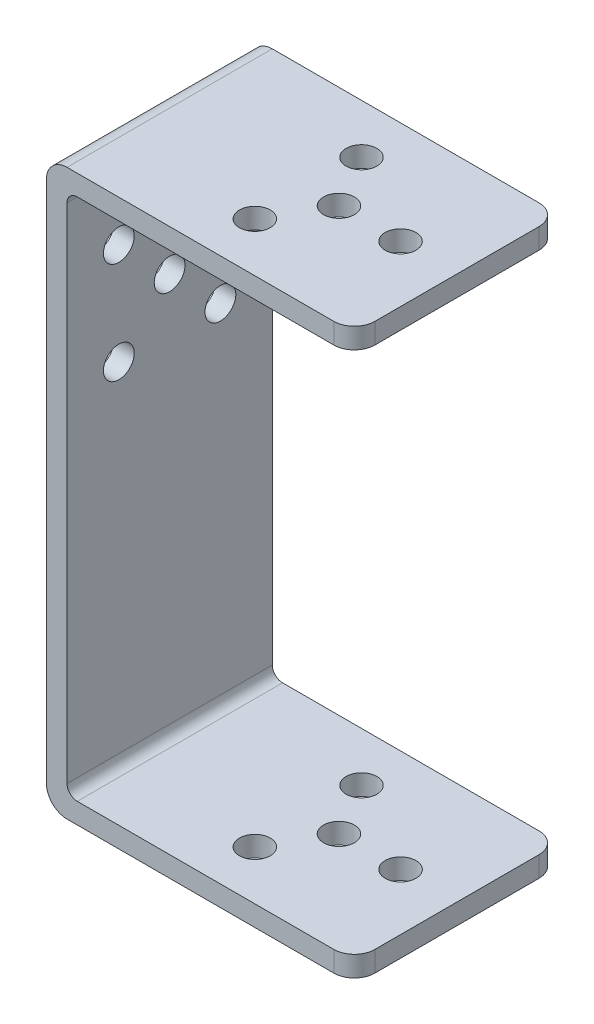
SolidWorks part; units mm, degrees
ref_plane "前视基准面" through (0, 0, 0) normal (0, 0, 1) x (1, 0, 0)
ref_plane "上视基准面" through (0, 0, 0) normal (0, 1, 0) x (1, 0, 0)
ref_plane "右视基准面" through (0, 0, 0) normal (1, 0, 0) x (0, 0, -1)
other "Configuration Table"
sketch "草图1" plane through (0, 0, 0) normal (0, 0, 1) x (1, 0, 0)
  line L0 (0, 0) -> (30, 0)
  line L1 (30, 0) -> (30, 2)
  line L2 (30, 2) -> (2, 2)
  line L3 (2, 2) -> (2, 53)
  line L4 (2, 53) -> (30, 53)
  line L5 (30, 53) -> (30, 55)
  line L6 (30, 55) -> (0, 55)
  line L7 (0, 55) -> (0, 0)
  dimension "D1" = 55
  dimension "D2" = 2
  dimension "D3" = 2
  dimension "D4" = 2
  dimension "D5" = 30
  dimension "D6" = 30
extrude "凸台-拉伸1" add sketch "草图1" along normal blind 20
sketch "草图2" plane through (0, 0, 0) normal (-1, 0, 0) x (0, 0, 1)
  line L0 (10, 55) -> (10, 0) construction
  line L1 (20, 55) -> (0, 55) construction
  line L2 (20, 0) -> (0, 0) construction
  line L3 (5.0503, 45.9497) -> (10, 41) construction
  circle A0 centre (10, 41) radius 1.5
  circle A1 centre (5.0503, 45.9497) radius 1.5
  circle A12 centre (14.9497, 45.9497) radius 1.5
  circle A13 centre (14.9497, 36.0503) radius 1.5
  circle A14 centre (5.0503, 36.0503) radius 1.5
  point P19 (10, 41)
  point P20 (10, 41)
  point P21 (10, 41)
  dimension "D3" = 3
  dimension "D4" = 3
  dimension "D1" = 41
  dimension "D2" = 45
  dimension "D5" = 7
  dimension "D6" = 4
extrude "切除-拉伸1" cut sketch "草图2" against normal blind 10
sketch "草图4" plane through (0, 55, 0) normal (0, 1, 0) x (1, 0, 0)
  line L0 (30, -20) -> (30, 0) construction
  line L1 (15, -10) -> (30, -10) construction
  line L2 (30, 0) -> (0, 0) construction
  circle A0 centre (18.5, -10) radius 1.5
  circle A1 centre (24.5, -10) radius 1.5
  circle A4 centre (15.5, -15.1962) radius 1.5
  circle A5 centre (15.5, -4.8038) radius 1.5
  point P15 (18.5, -10)
  point P18 (18.5, -10)
  dimension "D3" = 3
  dimension "D1" = 11.5
  dimension "D2" = 10
  dimension "D4" = 6
  dimension "D5" = 3
extrude "切除-拉伸2" cut sketch "草图4" against normal through all
fillet "圆角1" radius 2 2 edges at (0, 0, 10) (0, 55, 10)
fillet "圆角2" radius 1 2 edges at (2, 53, 10) (2, 2, 10)
fillet "圆角3" radius 2 4 edges at (30, 1, 0) (30, 1, 20) (30, 54, 0) (30, 54, 20)
